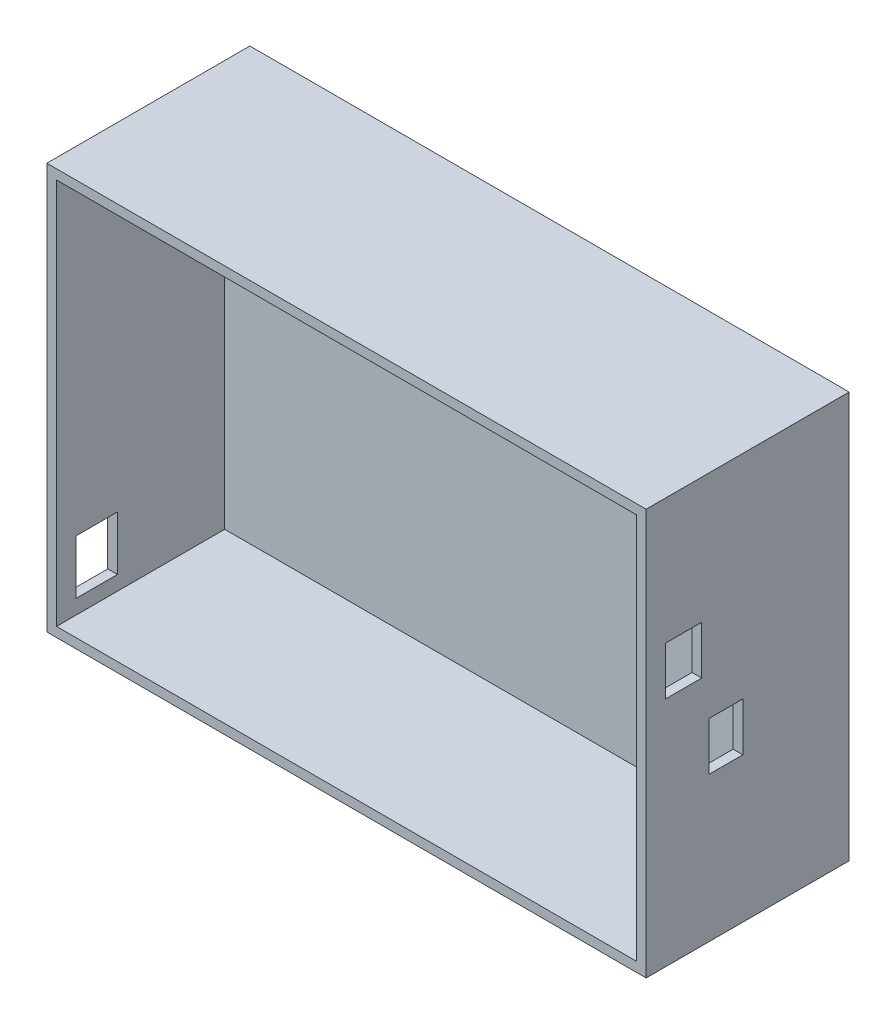
SolidWorks part; units mm, degrees
ref_plane "Front Plane" through (0, 0, 0) normal (0, 0, 1) x (1, 0, 0)
ref_plane "Top Plane" through (0, 0, 0) normal (0, 1, 0) x (1, 0, 0)
ref_plane "Right Plane" through (0, 0, 0) normal (1, 0, 0) x (0, 0, -1)
sketch "Sketch1" plane through (0, 0, 0) normal (0, 0, 1) x (1, 0, 0)
  line L1 (-78.74, -53.34) -> (78.74, -53.34)
  line L2 (-78.74, -53.34) -> (-78.74, 53.34)
  line L3 (-78.74, 53.34) -> (78.74, 53.34)
  line L4 (78.74, -53.34) -> (78.74, 53.34)
  line L5 (-78.74, -53.34) -> (78.74, 53.34) construction
  line L6 (-78.74, 53.34) -> (78.74, -53.34) construction
  point P0 (0, 0)
  dimension "D1" = 157.48
  dimension "D2" = 106.68
extrude "Boss-Extrude1" add sketch "Sketch1" along normal blind 53.34
sketch "Sketch3" plane through (0, 0, 53.34) normal (0, 0, 1) x (1, 0, 0)
  line L1 (-76.2, -50.8) -> (76.2, -50.8)
  line L2 (-76.2, -50.8) -> (-76.2, 50.8)
  line L3 (-76.2, 50.8) -> (76.2, 50.8)
  line L4 (76.2, -50.8) -> (76.2, 50.8)
  line L5 (-76.2, -50.8) -> (76.2, 50.8) construction
  line L6 (-76.2, 50.8) -> (76.2, -50.8) construction
  point P0 (0, 0)
  dimension "D1" = 152.4
  dimension "D2" = 101.6
extrude "Cut-Extrude1" cut sketch "Sketch3" against normal blind 44.196
sketch "Sketch4" plane through (78.74, 0, 0) normal (1, 0, 0) x (0, 0, -1)
  line L0 (-53.34, -53.34) -> (0, -53.34) construction
  line L1 (-36.83, -15.24) -> (-27.94, -15.24)
  line L2 (-36.83, -15.24) -> (-36.83, -2.54)
  line L3 (-36.83, -2.54) -> (-27.94, -2.54)
  line L4 (-27.94, -15.24) -> (-27.94, -2.54)
  line L5 (-36.83, -15.24) -> (-27.94, -2.54) construction
  line L6 (-36.83, -2.54) -> (-27.94, -15.24) construction
  line L7 (0, -53.34) -> (0, 53.34) construction
  point P0 (-32.385, -8.89)
  dimension "D1" = 12.7
  dimension "D2" = 8.89
  dimension "D3" = 38.1
  dimension "D4" = 27.94
extrude "Cut-Extrude2" cut sketch "Sketch4" against normal blind 43.18
sketch "Sketch6" plane through (-78.74, 0, 0) normal (-1, 0, 0) x (0, 0, 1)
  line L1 (37.338, -32.766) -> (48.26, -32.766)
  line L2 (37.338, -32.766) -> (37.338, -46.99)
  line L3 (37.338, -46.99) -> (48.26, -46.99)
  line L4 (48.26, -32.766) -> (48.26, -46.99)
  line L5 (37.338, -32.766) -> (48.26, -46.99) construction
  line L6 (37.338, -46.99) -> (48.26, -32.766) construction
  line L7 (53.34, -53.34) -> (0, -53.34) construction
  line L8 (53.34, 53.34) -> (53.34, -53.34) construction
  point P0 (42.799, -39.878)
  dimension "D1" = 14.224
  dimension "D2" = 10.922
  dimension "D3" = 5.08
  dimension "D4" = 6.35
extrude "Cut-Extrude3" cut sketch "Sketch6" against normal blind 43.18
sketch "Sketch7" plane through (78.74, 0, 0) normal (1, 0, 0) x (0, 0, -1)
  line L0 (-53.34, 53.34) -> (0, 53.34) construction
  line L1 (-48.26, 7.62) -> (-38.735, 7.62)
  line L2 (-48.26, 7.62) -> (-48.26, 20.32)
  line L3 (-48.26, 20.32) -> (-38.735, 20.32)
  line L4 (-38.735, 7.62) -> (-38.735, 20.32)
  line L5 (-48.26, 7.62) -> (-38.735, 20.32) construction
  line L6 (-48.26, 20.32) -> (-38.735, 7.62) construction
  line L7 (-53.34, -53.34) -> (-53.34, 53.34) construction
  point P0 (-43.4975, 13.97)
  dimension "D1" = 9.525
  dimension "D2" = 12.7
  dimension "D3" = 33.02
  dimension "D4" = 5.08
extrude "Cut-Extrude4" cut sketch "Sketch7" against normal blind 12.7
